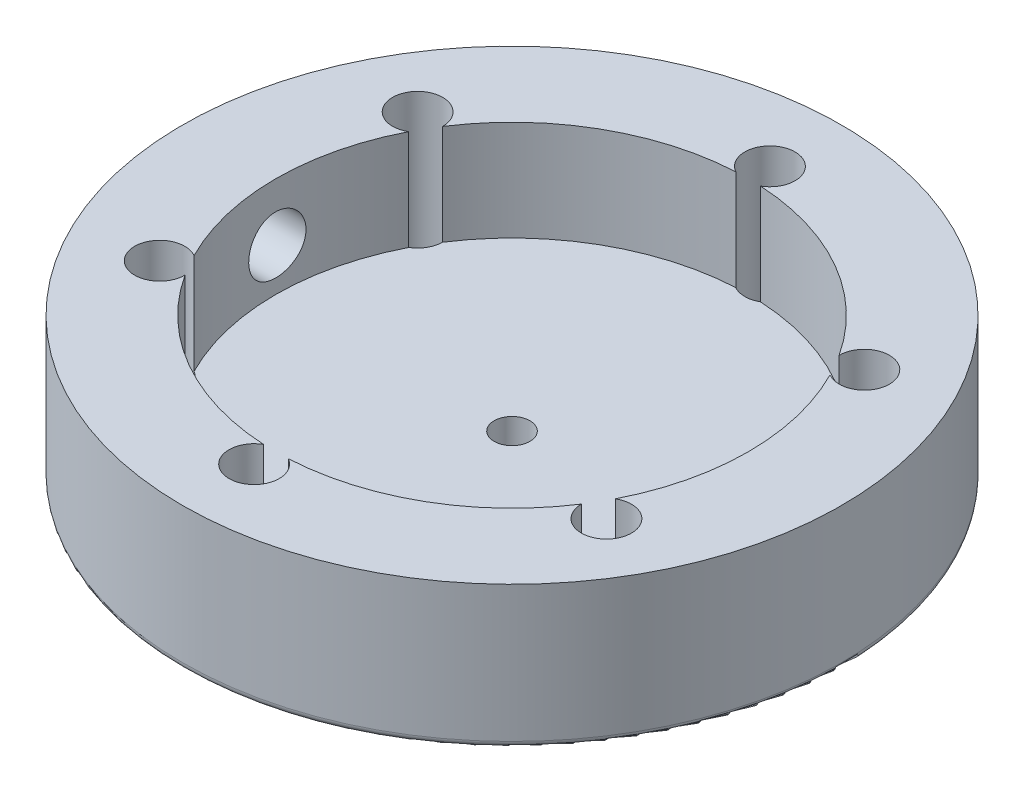
SolidWorks part; units mm, degrees
ref_plane "Front Plane" through (0, 0, 0) normal (0, 0, 1) x (1, 0, 0)
ref_plane "Top Plane" through (0, 0, 0) normal (0, 1, 0) x (1, 0, 0)
ref_plane "Right Plane" through (0, 0, 0) normal (1, 0, 0) x (0, 0, -1)
sketch "Sketch1" plane through (0, 0, 0) normal (0, 1, 0) x (1, 0, 0)
  circle A0 centre (0, 0) radius 46
  circle A1 centre (0, 0) radius 36 construction
  circle A2 centre (0, 36) radius 3.5
  circle A3 centre (-31.1769, 18) radius 3.5
  circle A4 centre (-31.1769, -18) radius 3.5
  circle A5 centre (0, -36) radius 3.5
  circle A6 centre (31.1769, -18) radius 3.5
  circle A7 centre (31.1769, 18) radius 3.5
  point P19 (0, 0)
  dimension "D1" = 6
extrude "Boss-Extrude1" add sketch "Sketch1" along normal blind 20
sketch "Sketch2" plane through (0, 20, 0) normal (0, 1, 0) x (1, 0, 0)
  circle A0 centre (0, 0) radius 33
extrude "Cut-Extrude1" cut sketch "Sketch2" against normal blind 14
fillet "Fillet2" radius 1 1 edges at (0, 0, 46)
sketch "Sketch3" plane through (0, 0, 0) normal (0, -1, 0) x (-1, 0, 0)
  circle A0 centre (0, 0) radius 12
extrude "Boss-Extrude2" add sketch "Sketch3" along normal blind 10
sketch "Sketch4" plane through (0, 6, 0) normal (0, 1, 0) x (1, 0, 0)
  circle A0 centre (0, 0) radius 2.5
extrude "Cut-Extrude2" cut sketch "Sketch4" against normal blind 6
sketch "Sketch5" plane through (0, -10, 0) normal (0, -1, 0) x (-1, 0, 0)
  circle A0 centre (0, 0) radius 5
extrude "Cut-Extrude3" cut sketch "Sketch5" against normal blind 10
cosmetic thread "Cosmetic Thread1" parameters "D1"=10, "D2"=16
chamfer "Chamfer1" distance 1 angle 45 1 edges at (0, -10, -5)
sketch "Sketch6" plane through (0, 0, 0) normal (1, 0, 0) x (0, 0, -1)
  line L0 (46, 20) -> (-46, 20) construction
  circle A0 centre (0, 12) radius 4
  dimension "D1" = 8
  dimension "D2" = 8
extrude "Cut-Extrude4" cut sketch "Sketch6" against normal through all
